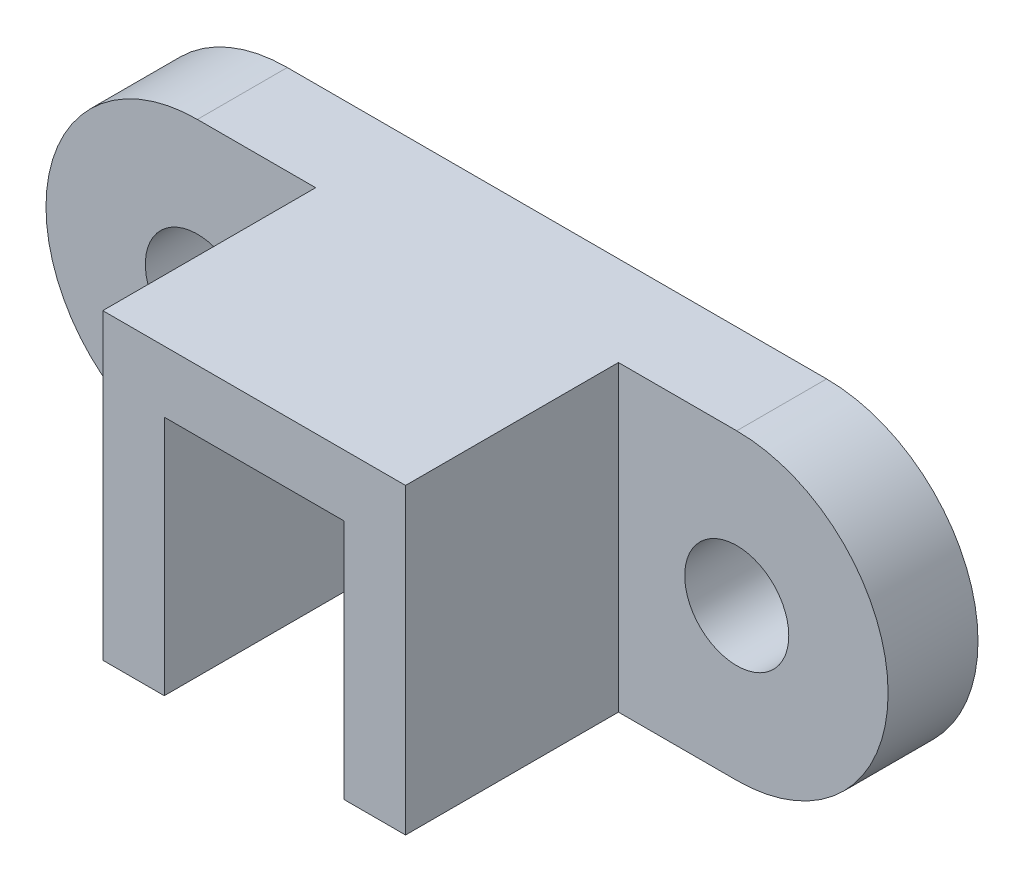
SolidWorks part; units mm, degrees
ref_plane "Front Plane" through (0, 0, 0) normal (0, 0, 1) x (1, 0, 0)
ref_plane "Top Plane" through (0, 0, 0) normal (0, 1, 0) x (1, 0, 0)
ref_plane "Right Plane" through (0, 0, 0) normal (1, 0, 0) x (0, 0, -1)
sketch "Sketch1" plane through (0, 0, 0) normal (0, 0, 1) x (1, 0, 0)
  line L0 (-57, 0) -> (57, 0) construction
  line L1 (-57, 32) -> (57, 32)
  line L2 (-57, -32) -> (57, -32)
  arc A0 (-57, 32) -> (-57, -32) centre (-57, 0) ccw
  arc A1 (57, -32) -> (57, 32) centre (57, 0) ccw
  point P2 (0, 0)
  dimension "D2" = 32
  dimension "D1" = 114
extrude "Boss-Extrude1" add sketch "Sketch1" along normal blind 19
sketch "Sketch2" plane through (0, 0, 19) normal (0, 0, 1) x (1, 0, 0)
  circle A0 centre (-57, 0) radius 11
  circle A1 centre (57, 0) radius 11
  dimension "D1" = 22
extrude "Cut-Extrude1" cut sketch "Sketch2" against normal through all
sketch "Sketch3" plane through (0, 0, 19) normal (0, 0, 1) x (1, 0, 0)
  line L0 (-32, 32) -> (-32, -32)
  line L1 (57, 32) -> (-57, 32) construction
  line L2 (-57, -32) -> (57, -32) construction
  line L3 (-32, -32) -> (32, -32)
  line L4 (32, -32) -> (32, 32)
  line L5 (32, 32) -> (-32, 32)
  line L6 (-32, 0) -> (-46, 0) construction
  line L7 (46, 0) -> (32, 0) construction
  circle A0 centre (-57, 0) radius 11 construction
  circle A1 centre (57, 0) radius 11 construction
  dimension "D1" = 64
extrude "Boss-Extrude2" add sketch "Sketch3" along normal blind 45
sketch "Sketch4" plane through (0, -32, 0) normal (0, -1, 0) x (1, 0, 0)
  line L0 (-19, 64) -> (-19, 13)
  line L1 (-32, 64) -> (32, 64) construction
  line L2 (-19, 13) -> (19, 13)
  line L3 (19, 13) -> (19, 64)
  line L4 (19, 64) -> (-19, 64)
  line L5 (-57, 0) -> (57, 0) construction
  line L6 (-19, 38.5) -> (-32, 38.5) construction
  line L7 (-32, 64) -> (-32, 19) construction
  line L8 (19, 38.5) -> (32, 38.5) construction
  line L9 (32, 64) -> (32, 19) construction
  dimension "D1" = 13
  dimension "D2" = 38
extrude "Cut-Extrude2" cut sketch "Sketch4" against normal blind 51
sketch "Sketch5" plane through (19, 0, 0) normal (-1, 0, 0) x (0, 0, 1)
  line L0 (64, 19) -> (13, -32)
  line L1 (13, -32) -> (13, 19)
  line L2 (13, 19) -> (64, 19)
extrude "Boss-Extrude3" add sketch "Sketch5" along normal blind 38
